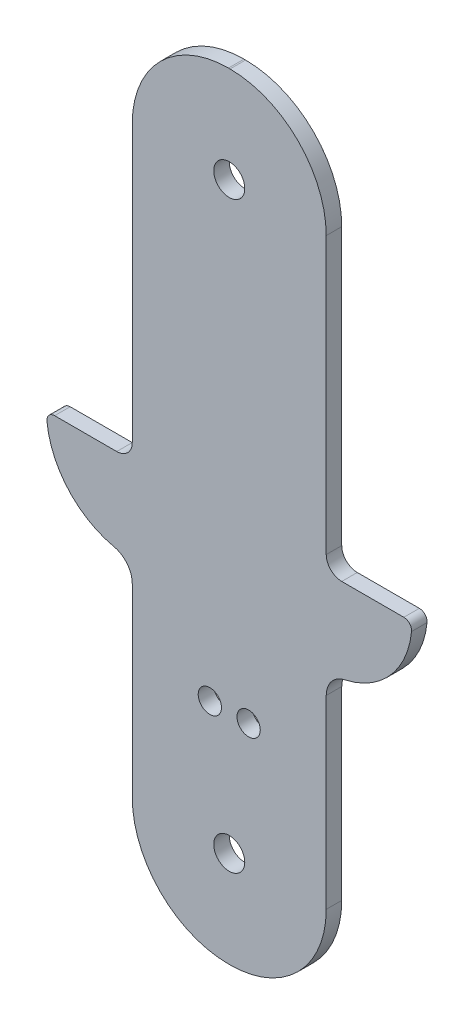
SolidWorks part; units mm, degrees
ref_plane "Front Plane" through (0, 0, 0) normal (0, 0, 1) x (1, 0, 0)
ref_plane "Top Plane" through (0, 0, 0) normal (0, 1, 0) x (1, 0, 0)
ref_plane "Right Plane" through (0, 0, 0) normal (1, 0, 0) x (0, 0, -1)
sketch "Sketch1" plane through (0, 0, 0) normal (0, 0, 1) x (1, 0, 0)
  line L0 (0, 50) -> (70.2451, 50) construction
  line L1 (12.4, 0) -> (12.6, 0)
  line L2 (0, 12.4) -> (0, 36.2741)
  line L3 (12.4, 100) -> (12.6, 100)
  line L4 (25, 12.4) -> (25, 36.2741)
  line L5 (-2, 50) -> (-10, 50)
  line L6 (12.5, 0) -> (12.5, 34.9925) construction
  line L7 (27, 50) -> (35, 50)
  line L8 (0, 52) -> (0, 87.6)
  line L9 (25, 52) -> (25, 87.6)
  arc A0 (-10.995, 48.9005) -> (-2.3594, 39.205) centre (0, 50) ccw
  arc A1 (-10, 50) -> (-10.995, 48.9005) centre (-10, 49) ccw
  arc A2 (35, 50) -> (35.995, 48.9005) centre (35, 49) cw
  arc A3 (35.995, 48.9005) -> (27.3594, 39.205) centre (25, 50) cw
  circle A4 centre (12.5, 12.4) radius 7.5 construction
  arc A5 (27.3594, 39.205) -> (25, 36.2741) centre (28, 36.2741) ccw
  arc A6 (-2.3594, 39.205) -> (0, 36.2741) centre (-3, 36.2741) cw
  arc A7 (27, 50) -> (25, 52) centre (27, 52) cw
  arc A8 (-2, 50) -> (0, 52) centre (-2, 52) ccw
  arc A9 (12.6, 0) -> (25, 12.4) centre (12.6, 12.4) ccw
  arc A10 (12.4, 0) -> (0, 12.4) centre (12.4, 12.4) cw
  arc A11 (12.6, 100) -> (25, 87.6) centre (12.6, 87.6) cw
  arc A12 (0, 87.6) -> (12.4, 100) centre (12.4, 87.6) cw
  circle A13 centre (12.5, 87.6) radius 2
  circle A14 centre (12.5, 12.4) radius 2
  circle A15 centre (10, 28.1534) radius 1.5
  circle A16 centre (15, 28.1534) radius 1.5
  point P23 (25, 38.9501)
  point P26 (0, 38.9501)
  point P37 (0, 0)
  point P40 (25, 100)
  point P43 (0, 100)
  dimension "D3" = 1
  dimension "D4" = 15
  dimension "D5" = 3
  dimension "D6" = 2
  dimension "D7" = 12.4
  dimension "D8" = 12.4
  dimension "D9" = 4
  dimension "D10" = 4
  dimension "D11" = 3
  dimension "D12" = 3
  dimension "D1" = 100
  dimension "D2" = 25
  dimension "D13" = 2.5
  dimension "D14" = 2.5
  dimension "D15" = 8
extrude "Boss-Extrude1" add sketch "Sketch1" along normal blind 2
